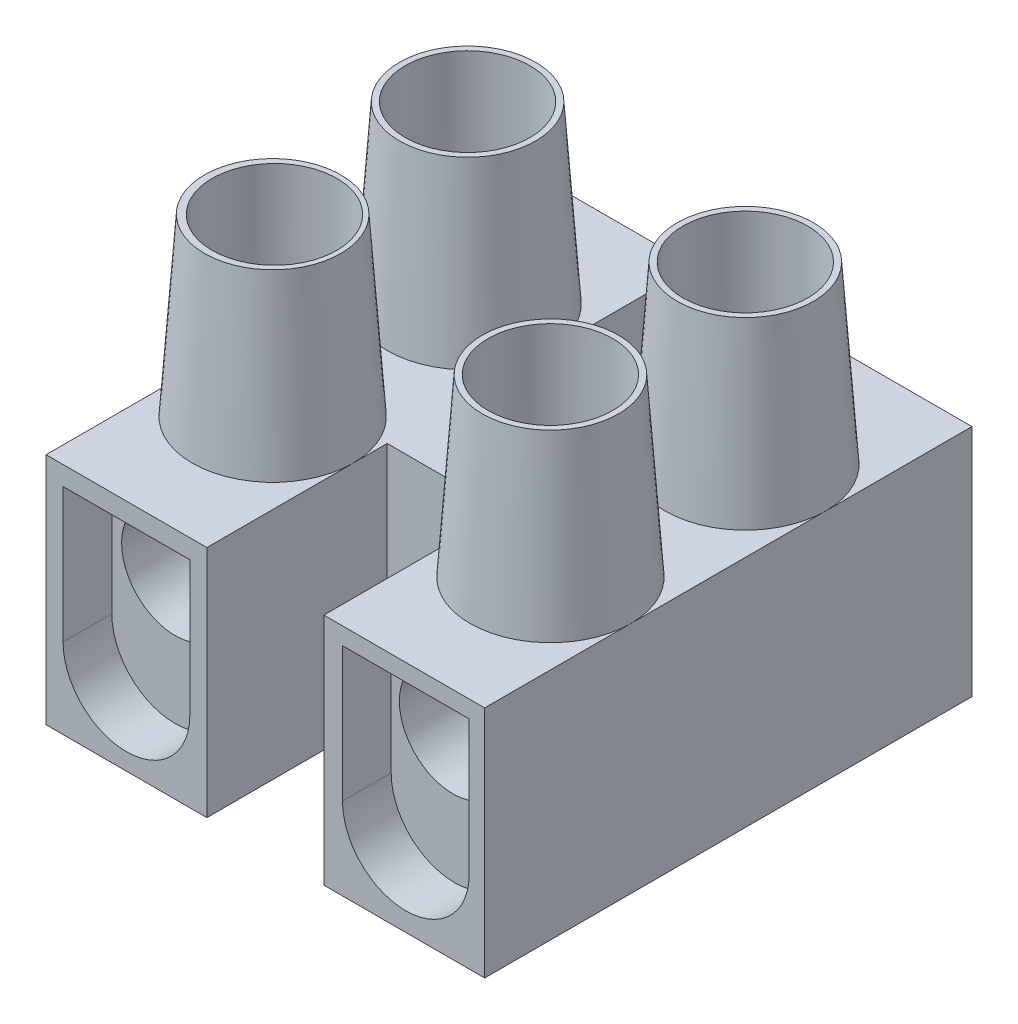
SolidWorks part; units mm, degrees
ref_plane "Front Plane" through (0, 0, 0) normal (0, 0, 1) x (1, 0, 0)
ref_plane "Top Plane" through (0, 0, 0) normal (0, 1, 0) x (1, 0, 0)
ref_plane "Right Plane" through (0, 0, 0) normal (1, 0, 0) x (0, 0, -1)
sketch "Sketch1" plane through (0, 0, 0) normal (0, 0, 1) x (1, 0, 0)
  line L1 (-45, 24) -> (45, 24)
  line L2 (-45, 24) -> (-45, -24)
  line L3 (-45, -24) -> (45, -24)
  line L4 (45, 24) -> (45, -24)
  line L5 (-45, 24) -> (45, -24) construction
  line L6 (-45, -24) -> (45, 24) construction
  point P0 (0, 0)
  dimension "D1" = 48
  dimension "D2" = 90
extrude "Boss-Extrude1" add sketch "Sketch1" along normal mid plane 100
sketch "Sketch2" plane through (0, 24, 0) normal (0, 1, 0) x (1, 0, 0)
  line L0 (45, 50) -> (-45, 50) construction
  line L1 (-12, 50) -> (12, 50)
  line L2 (-12, 50) -> (-12, 13)
  line L3 (-12, 13) -> (12, 13)
  line L4 (12, 50) -> (12, 13)
  line L5 (-45, -50) -> (-45, 50) construction
  line L6 (45, -50) -> (45, 50) construction
  dimension "D1" = 24
  dimension "D2" = 33
  dimension "D3" = 33
  dimension "D4" = 37
extrude "Cut-Extrude1" cut sketch "Sketch2" against normal blind 100
sketch "Sketch3" plane through (0, 24, 0) normal (0, 1, 0) x (1, 0, 0)
  line L0 (45, -50) -> (-45, -50) construction
  line L1 (-12, -13) -> (12, -13)
  line L2 (-12, -13) -> (-12, -50)
  line L3 (-12, -50) -> (12, -50)
  line L4 (12, -13) -> (12, -50)
  line L5 (-45, -50) -> (-45, 50) construction
  line L6 (45, -50) -> (45, 50) construction
  dimension "D1" = 33
  dimension "D2" = 33
  dimension "D3" = 37
extrude "Cut-Extrude2" cut sketch "Sketch3" against normal blind 100
sketch "Sketch4" plane through (0, 24, 0) normal (0, 1, 0) x (1, 0, 0)
  circle A0 centre (0, 0) radius 8.5755
extrude "Cut-Extrude3" cut sketch "Sketch4" against normal blind 100
sketch "Sketch5" plane through (0, 24, 0) normal (0, 1, 0) x (1, 0, 0)
  line L0 (45, 50) -> (12, 50) construction
  line L1 (-45, -50) -> (-45, 50) construction
  line L2 (45, -50) -> (45, 50) construction
  line L3 (-12, 50) -> (-45, 50) construction
  line L4 (45, -50) -> (12, -50) construction
  line L5 (-12, -50) -> (-45, -50) construction
  circle A0 centre (28.5, 20) radius 16.5
  circle A1 centre (-28.5, 20) radius 16.5
  circle A2 centre (-28.5, -20) radius 16.5
  circle A3 centre (28.5, -20) radius 16.5
  point P20 (0, 0)
  point P21 (0, 0)
  point P22 (-45, -26.5483)
  point P23 (-45, -41.7713)
  dimension "D2" = 33
  dimension "D3" = 33
  dimension "D7" = 33
  dimension "D8" = 33
  dimension "D1" = 30
  dimension "D4" = 16.5
  dimension "D5" = 16.5
  dimension "D6" = 30
  dimension "D9" = 30
  dimension "D10" = 30
extrude "Boss-Extrude2" add sketch "Sketch5" along normal blind 36 draft 4
sketch "Sketch6" plane through (0, 60, 0) normal (0, 1, 0) x (1, 0, 0)
  circle A0 centre (-28.5, 20) radius 12.8
  dimension "D1" = 25.6
extrude "Cut-Extrude4" cut sketch "Sketch6" against normal blind 30
sketch "Sketch10" plane through (0, 60, 0) normal (0, 1, 0) x (1, 0, 0)
  circle A0 centre (-28.2752, -19.8517) radius 12.8
  circle A1 centre (28.5, -20) radius 12.8
  circle A2 centre (28.5, 20) radius 12.8
  dimension "D1" = 25.6
  dimension "D2" = 25.6
  dimension "D3" = 25.6
extrude "Cut-Extrude5" cut sketch "Sketch10" against normal blind 30
sketch "Sketch12" plane through (0, 30, 0) normal (0, 1, 0) x (1, 0, 0)
  line L1 (26.7833, 33.1487) -> (30.2167, 33.1487)
  line L2 (26.7833, 33.1487) -> (26.7833, 6.8513)
  line L3 (26.7833, 6.8513) -> (30.2167, 6.8513)
  line L4 (30.2167, 33.1487) -> (30.2167, 6.8513)
  line L5 (26.7833, 33.1487) -> (30.2167, 6.8513) construction
  line L6 (26.7833, 6.8513) -> (30.2167, 33.1487) construction
  line L7 (-30.215, 32.6846) -> (-26.785, 32.6846)
  line L8 (-30.215, 32.6846) -> (-30.215, 7.3154)
  line L9 (-30.215, 7.3154) -> (-26.785, 7.3154)
  line L10 (-26.785, 32.6846) -> (-26.785, 7.3154)
  line L11 (-30.215, 32.6846) -> (-26.785, 7.3154) construction
  line L12 (-30.215, 7.3154) -> (-26.785, 32.6846) construction
  line L13 (-30.4962, -7.1915) -> (-27.0662, -7.1915)
  line L14 (-30.4962, -7.1915) -> (-30.4962, -35.0988)
  line L15 (-30.4962, -35.0988) -> (-27.0662, -35.0988)
  line L16 (-27.0662, -7.1915) -> (-27.0662, -35.0988)
  line L17 (-30.4962, -7.1915) -> (-27.0662, -35.0988) construction
  line L18 (-30.4962, -35.0988) -> (-27.0662, -7.1915) construction
  line L19 (26.7833, -7.1915) -> (30.2167, -7.1915)
  line L20 (26.7833, -7.1915) -> (26.7833, -35.0988)
  line L21 (26.7833, -35.0988) -> (30.2167, -35.0988)
  line L22 (30.2167, -7.1915) -> (30.2167, -35.0988)
  line L23 (26.7833, -7.1915) -> (30.2167, -35.0988) construction
  line L24 (26.7833, -35.0988) -> (30.2167, -7.1915) construction
  circle A0 centre (-28.5, 20) radius 12.8 construction
  point P0 (28.5, 20)
  point P6 (-28.5, 20)
  point P14 (-28.7812, -21.1452)
  point P19 (28.5, -21.1452)
  dimension "D1" = 3.4333
  dimension "D2" = 3.4333
  dimension "D3" = 3.43
  dimension "D4" = 3.43
extrude "Cut-Extrude6" cut sketch "Sketch12" against normal blind 3
sketch "Sketch13" plane through (0, 0, 0) normal (0, 0, 1) x (1, 0, 0)
  line L0 (-15.4992, -7.5318) -> (-15.4992, 20.0904)
  line L1 (-41.5093, 20.0904) -> (-15.4992, 20.0904)
  line L2 (-41.5093, 20.0904) -> (-41.5093, -7.5318)
  line L5 (41.8274, 20.4742) -> (41.8274, -7.1438)
  line L6 (15.8274, 20.4742) -> (41.8274, 20.4742)
  line L7 (-45, 24) -> (-45, -24) construction
  line L8 (15.8274, 20.4742) -> (15.8274, -7.1438)
  line L9 (45, -24) -> (45, 24) construction
  line L15 (-15.4992, 20.0904) -> (-15.4992, -7.5318)
  line L19 (12, -24) -> (45, -24)
  line L20 (12, 24) -> (12, -24)
  line L21 (45, 24) -> (12, 24)
  line L22 (45, -24) -> (45, 24)
  line L23 (12, -24) -> (45, -24)
  line L24 (12, 24) -> (12, -24)
  line L25 (45, 24) -> (12, 24)
  line L26 (45, -24) -> (45, 24)
  arc A0 (-41.5093, -7.5318) -> (-15.4992, -7.5318) centre (-28.5042, -7.5318) ccw
  arc A1 (15.8274, -7.1438) -> (41.8274, -7.1438) centre (28.8274, -7.1438) ccw
  point P0 (-28.5, -0.2252)
  point P9 (28.5, 0.1652)
  dimension "D5" = 26.0101
  dimension "D6" = 0
  dimension "D9" = 20.0904
  dimension "D1" = 13
  dimension "D2" = 16.5
  dimension "D3" = 16.5
  dimension "D4" = 15.8274
  dimension "D7" = 15.4992
  dimension "D8" = 0.1652
  dimension "D11" = 0.2252
  dimension "D12" = 7.5318
extrude "Cut-Extrude9" cut sketch "Sketch13" against normal through all both and the other way through all contours L2 A0 L0 L1 | L8 A1 L5 L6
sketch "Sketch18" plane through (0, 0, 0) normal (0, 0, 1) x (1, 0, 0)
  line L1 (42.2187, 22.1728) -> (15.3411, 22.1728)
  line L2 (42.2187, 22.1728) -> (42.2187, -20.7823)
  line L3 (42.2187, -20.7823) -> (15.3411, -20.7823)
  line L4 (15.3411, 22.1728) -> (15.3411, -20.7823)
  line L5 (42.2187, 22.1728) -> (15.3411, -20.7823) construction
  line L6 (42.2187, -20.7823) -> (15.3411, 22.1728) construction
  line L7 (-14.9729, 20.5773) -> (-42.2513, 20.5773)
  line L8 (-14.9729, 20.5773) -> (-14.9729, -20.9256)
  line L9 (-14.9729, -20.9256) -> (-42.2513, -20.9256)
  line L10 (-42.2513, 20.5773) -> (-42.2513, -20.9256)
  line L11 (-14.9729, 20.5773) -> (-42.2513, -20.9256) construction
  line L12 (-14.9729, -20.9256) -> (-42.2513, 20.5773) construction
  point P0 (28.7799, 0.6952)
  point P5 (-28.6121, -0.1741)
  point P10 (-41.2369, 20.5773)
  point P11 (0, 0)
  point P12 (0, 0)
  point P13 (0, 0)
  point P14 (0, 0)
  point P15 (-14.9729, -20.6596)
  point P16 (0, 0)
  point P17 (0, 0)
  point P18 (0, 0)
  point P19 (42.2187, 22.1728)
  point P20 (15.3411, -20.7823)
  point P21 (0, 0)
  point P22 (0, 0)
  point P23 (0, 0)
  point P24 (0, 0)
  point P25 (0, 0)
  point P26 (0, 0)
  point P27 (-43.3296, -20.3265)
  point P28 (0, 0)
  point P29 (0, 0)
  point P30 (0, 0)
  point P31 (0, 0)
  point P32 (0, 0)
  point P33 (-42.2513, -20.9256)
extrude "Boss-Extrude3" add sketch "Sketch18" along normal blind 40 and the other way blind 40 separate body
sketch "Sketch19" plane through (0, 0, -40) normal (0, 0, -1) x (-1, 0, 0)
  line L0 (-15.8274, 20.4742) -> (-41.8274, 20.4742) construction
  line L1 (-45, -24) -> (-45, 24) construction
  line L2 (41.5093, 20.0904) -> (15.4992, 20.0904) construction
  line L3 (45, 24) -> (45, -24) construction
  circle A0 centre (-28.5, 6.4742) radius 11
  circle A1 centre (28.5, 6.0904) radius 11
  dimension "D3" = 22
  dimension "D4" = 22
  dimension "D1" = 14
  dimension "D2" = 16.5
  dimension "D5" = 14
  dimension "D6" = 16.5
extrude "Cut-Extrude10" cut sketch "Sketch19" against normal through all both and the other way through all
